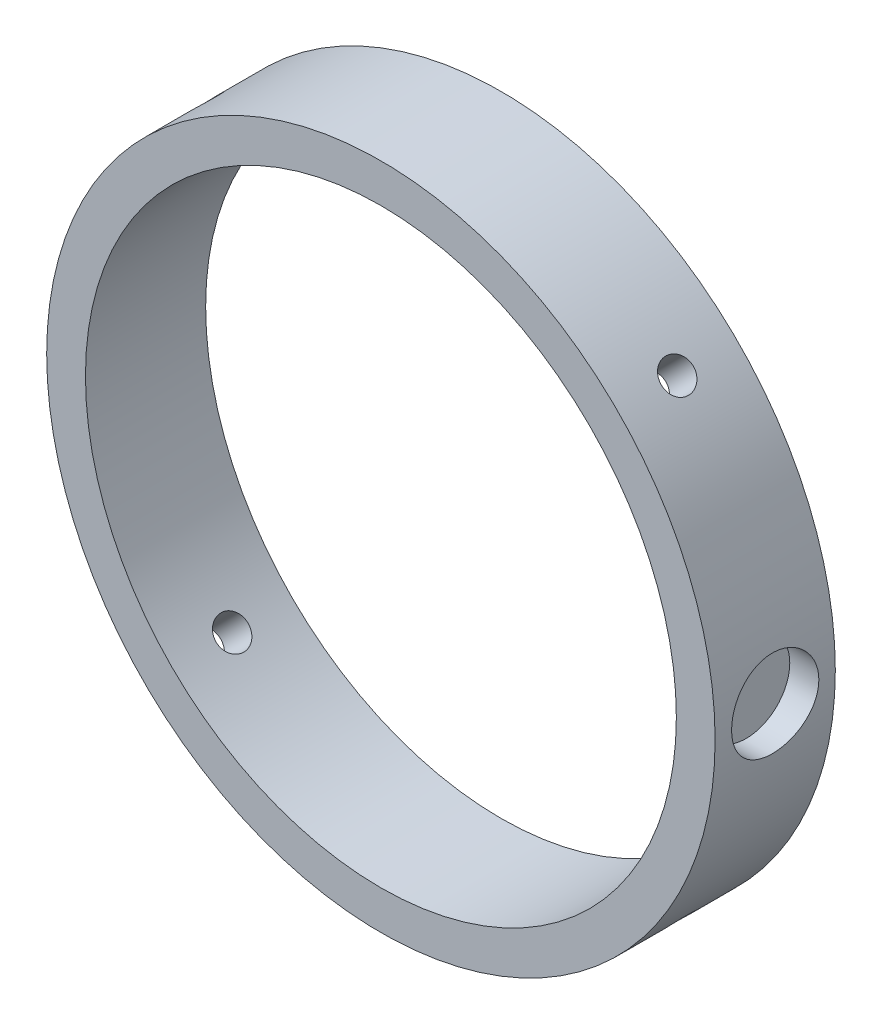
SolidWorks part; units mm, degrees
ref_plane "Plano frontal" through (0, 0, 0) normal (0, 0, 1) x (1, 0, 0)
ref_plane "Plano superior" through (0, 0, 0) normal (0, 1, 0) x (1, 0, 0)
ref_plane "Plano direito" through (0, 0, 0) normal (1, 0, 0) x (0, 0, -1)
sketch "Esboço2" plane through (0, 0, 0) normal (0, 0, 1) x (1, 0, 0)
  circle A0 centre (0, 0) radius 76.2
  circle A1 centre (0, 0) radius 86.2
  dimension "D1" = 152.4
  dimension "D2" = 172.4
extrude "Ressalto-extrusão1" add sketch "Esboço2" along normal blind 31
ref_plane "Plano1" through (86.2, 0, 0) normal (1, 0, 0) x (0, 0, -1)
ref_plane "Plano2" through (0, 0, 15.5) normal (0, 0, 1) x (1, 0, 0)
sketch "Esboço4" plane through (0, 0, 15.5) normal (0, 0, 1) x (1, 0, 0)
  line L0 (-86.2, 0) -> (0, 0) construction
  circle A0 centre (0, 0) radius 86.2 construction
  point P0 (-60.9526, 60.9526)
  point P1 (60.9526, 60.9526)
  point P4 (60.9526, -60.9526)
  point P5 (-60.9526, -60.9526)
  dimension "D1" = 90
  dimension "D2" = 90
  dimension "D3" = 90
  dimension "D4" = 45
hole_wizard "Furo roscado para conduíte de M8x1.252" positions "3DSketch4" profile "Esboço7" tap size "M8x1.25" standard "Helicoil® Metric" end condition up to next
sketch3d "3DSketch4"
  point P0 (-60.9526, 60.9526, 15.5)
  point P3 (-60.9526, 60.9526, 15.5)
  point P5 (60.9526, 60.9526, 15.5)
  point P7 (-60.9526, -60.9526, 15.5)
  point P9 (60.9526, -60.9526, 15.5)
  point P12 (60.9526, -60.9526, 15.5)
sketch "Esboço7" plane through (60.9526, -60.9526, 15.5) normal (0, 0, 1) x (0.7071, 0.7071, 0)
  line L0 (0, 0) -> (0, 86.2)
  line L1 (0, 86.2) -> (4.15, 86.2)
  line L2 (4.15, 86.2) -> (4.15, 0)
  line L5 (4.15, 0) -> (0, 0)
  line L11 (0, -6.35) -> (0, 107.95) construction
  dimension "Thru Tap Drill Dia." = 8.3
  dimension "Thru Tap Drill Depth" = 86.2
cosmetic thread "Rosca de furo1" parameters "D1"=10, "D2"=9.787
cosmetic thread "Rosca de furo2" parameters "D1"=10, "D2"=9.787
cosmetic thread "Rosca de furo3" parameters "D1"=10, "D2"=9.787
cosmetic thread "Rosca de furo4" parameters "D1"=10, "D2"=9.787
ref_plane "Plano3" through (79.2, 0, 0) normal (-1, 0, 0) x (0, 0, 1)
sketch "Esboço11" plane through (86.2, 0, 0) normal (1, 0, 0) x (0, 0, -1)
  line L0 (-15.5, 94.82) -> (-15.5, -94.82) construction
  line L1 (17.05, 0) -> (-17.05, 0) construction
  circle A0 centre (-15.5, 0) radius 11.25
  dimension "D1" = 22.5
extrude "Corte-extrusão1" cut sketch "Esboço11" against normal blind 7.5
mirror "Espelhar1" about plane through (0, 0, 0) normal (1, 0, 0) of "Corte-extrusão1"
